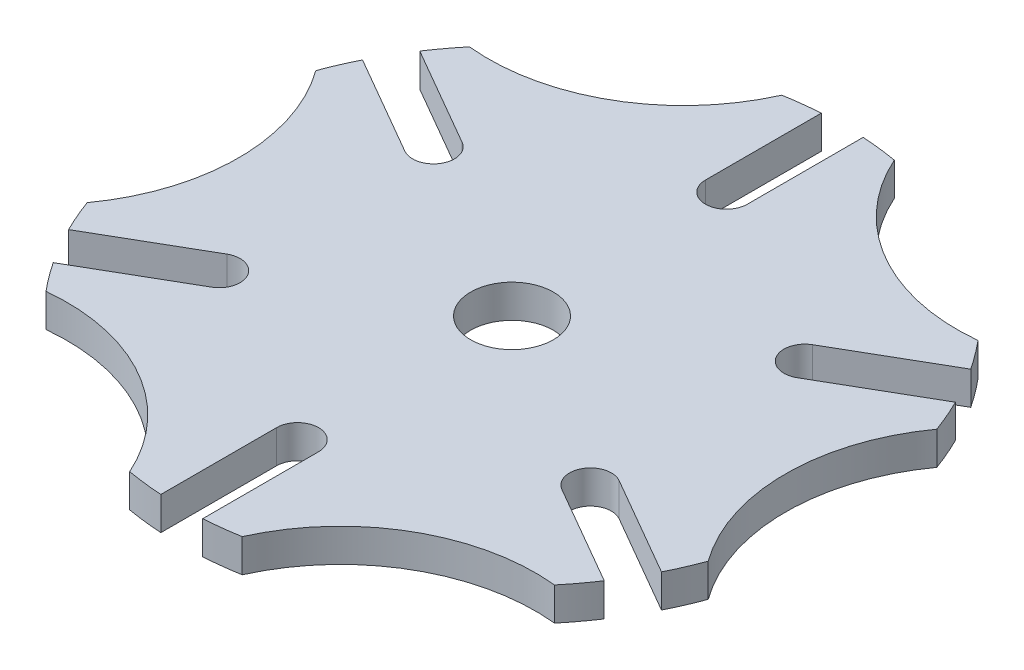
SolidWorks part; units mm, degrees
ref_plane "Front Plane" through (0, 0, 0) normal (0, 0, 1) x (1, 0, 0)
ref_plane "Top Plane" through (0, 0, 0) normal (0, 1, 0) x (1, 0, 0)
ref_plane "Right Plane" through (0, 0, 0) normal (1, 0, 0) x (0, 0, -1)
sketch "Sketch1" plane through (0, 0, 0) normal (0, 1, 0) x (1, 0, 0)
  line L0 (0, 100.6591) -> (0, 0) construction
  line L1 (-4.826, 49.377) -> (-4.826, 76.047)
  line L2 (4.826, 49.377) -> (4.826, 76.047)
  line L3 (40.3488, 28.868) -> (63.4457, 42.203)
  line L4 (45.1748, 20.5091) -> (68.2717, 33.8441)
  line L5 (45.1748, -20.5091) -> (68.2717, -33.8441)
  line L6 (40.3488, -28.868) -> (63.4457, -42.203)
  line L7 (4.826, -49.377) -> (4.826, -76.047)
  line L8 (-4.826, -49.377) -> (-4.826, -76.047)
  line L9 (-40.3488, -28.868) -> (-63.4457, -42.203)
  line L10 (-45.1748, -20.5091) -> (-68.2717, -33.8441)
  line L11 (-45.1748, 20.5091) -> (-68.2717, 33.8441)
  line L12 (-40.3488, 28.868) -> (-63.4457, 42.203)
  line L13 (0, 0) -> (-107.95, 0) construction
  arc A0 (-68.2717, 33.8441) -> (-71.5073, 26.3277) centre (0, 0) ccw
  circle A1 centre (0, 0) radius 9.525
  arc A2 (-4.826, 49.377) -> (4.826, 49.377) centre (0, 49.377) ccw
  arc A3 (40.3488, 28.868) -> (45.1748, 20.5091) centre (42.7618, 24.6885) ccw
  arc A4 (45.1748, -20.5091) -> (40.3488, -28.868) centre (42.7618, -24.6885) ccw
  arc A5 (4.826, -49.377) -> (-4.826, -49.377) centre (0, -49.377) ccw
  arc A6 (-40.3488, -28.868) -> (-45.1748, -20.5091) centre (-42.7618, -24.6885) ccw
  arc A7 (-45.1748, 20.5091) -> (-40.3488, 28.868) centre (-42.7618, 24.6885) ccw
  arc A8 (-4.826, 76.047) -> (-12.9532, 75.091) centre (0, 0) ccw
  arc A9 (63.4457, 42.203) -> (58.5541, 48.7632) centre (0, 0) ccw
  arc A10 (68.2717, -33.8441) -> (71.5073, -26.3277) centre (0, 0) ccw
  arc A11 (4.826, -76.047) -> (12.9532, -75.091) centre (0, 0) ccw
  arc A12 (-63.4457, -42.203) -> (-58.5541, -48.7632) centre (0, 0) ccw
  arc A13 (-71.5073, 26.3277) -> (-71.5073, -26.3277) centre (-107.95, 0) cw
  arc A14 (-12.9532, 75.091) -> (-58.5541, 48.7632) centre (-53.975, 93.4874) cw
  arc A15 (58.5541, 48.7632) -> (12.9532, 75.091) centre (53.975, 93.4874) cw
  arc A16 (71.5073, -26.3277) -> (71.5073, 26.3277) centre (107.95, 0) cw
  arc A17 (12.9532, -75.091) -> (58.5541, -48.7632) centre (53.975, -93.4874) cw
  arc A18 (-58.5541, -48.7632) -> (-12.9532, -75.091) centre (-53.975, -93.4874) cw
  arc A19 (-71.5073, -26.3277) -> (-68.2717, -33.8441) centre (0, 0) ccw
  arc A20 (-58.5541, 48.7632) -> (-63.4457, 42.203) centre (0, 0) ccw
  arc A21 (12.9532, 75.091) -> (4.826, 76.047) centre (0, 0) ccw
  arc A22 (71.5073, 26.3277) -> (68.2717, 33.8441) centre (0, 0) ccw
  arc A23 (58.5541, -48.7632) -> (63.4457, -42.203) centre (0, 0) ccw
  arc A24 (-12.9532, -75.091) -> (-4.826, -76.047) centre (0, 0) ccw
  point P38 (0, 0)
  point P55 (0, 0)
  dimension "D1" = 152.4
  dimension "D2" = 19.05
  dimension "D3" = 4.826
  dimension "D7" = 44.958
  dimension "D4" = 26.67
  dimension "D6" = 107.95
  dimension "D5" = 6
  dimension "D8" = 6
extrude "Boss-Extrude1" add sketch "Sketch1" along normal blind 7.62
